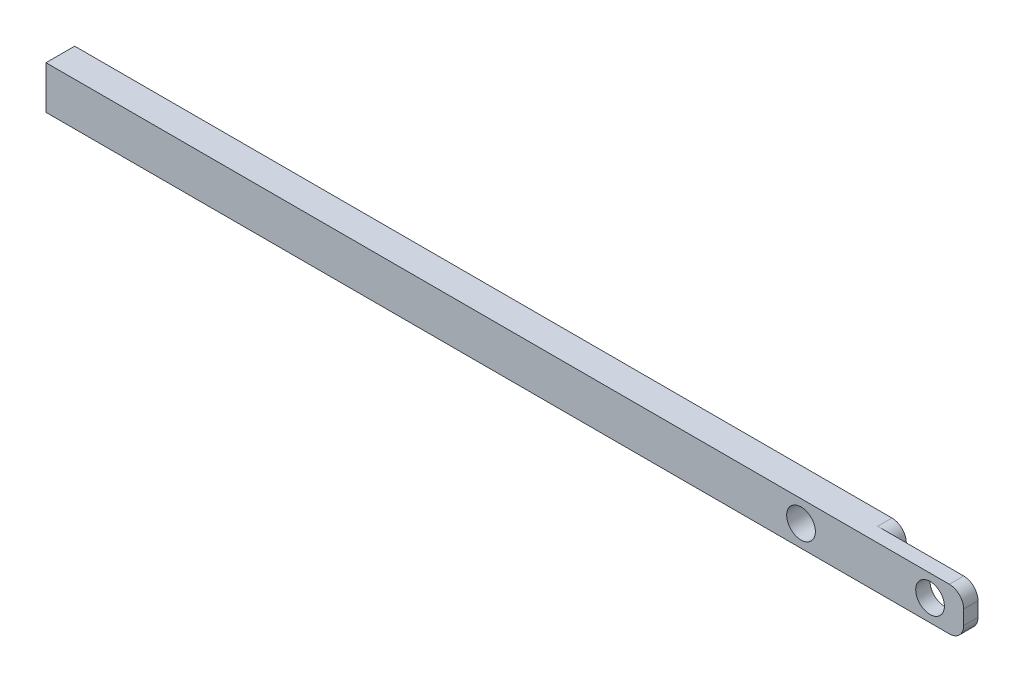
SolidWorks part; units mm, degrees
ref_plane "Front Plane" through (0, 0, 0) normal (0, 0, 1) x (1, 0, 0)
ref_plane "Top Plane" through (0, 0, 0) normal (0, 1, 0) x (1, 0, 0)
ref_plane "Right Plane" through (0, 0, 0) normal (1, 0, 0) x (0, 0, -1)
sketch "Sketch1" plane through (0, 0, 0) normal (0, 1, 0) x (1, 0, 0)
  line L1 (-637.6119, 61.791) -> (-57.6119, 61.791)
  line L2 (-637.6119, 61.791) -> (-637.6119, 41.791)
  line L3 (-637.6119, 41.791) -> (-17.6119, 41.791)
  line L4 (-57.6119, 61.791) -> (-57.6119, 51.791)
  line L5 (-17.6119, 41.791) -> (2.3881, 41.791)
  line L7 (-57.6119, 51.791) -> (2.3881, 51.791)
  line L8 (2.3881, 41.791) -> (2.3881, 51.791)
  dimension "D1" = 580
  dimension "D2" = 20
  dimension "D3" = 10
  dimension "D4" = 20
  dimension "D5" = 620
extrude "Boss-Extrude1" add sketch "Sketch1" along normal blind 30
fillet "Fillet1" radius 10 4 edges at (-57.6119, 0, -56.791) (-57.6119, 30, -56.791) (2.3881, 0, -46.791) (2.3881, 30, -46.791)
sketch "Sketch2" plane through (0, 0, -41.791) normal (0, 0, 1) x (1, 0, 0)
  line L0 (2.3881, 20) -> (2.3881, 10) construction
  circle A0 centre (-21.0464, 15) radius 10
  circle A1 centre (-111.0464, 15) radius 10
  point P5 (2.3881, 15)
  dimension "D1" = 20
extrude "Cut-Extrude1" cut sketch "Sketch2" against normal through all
